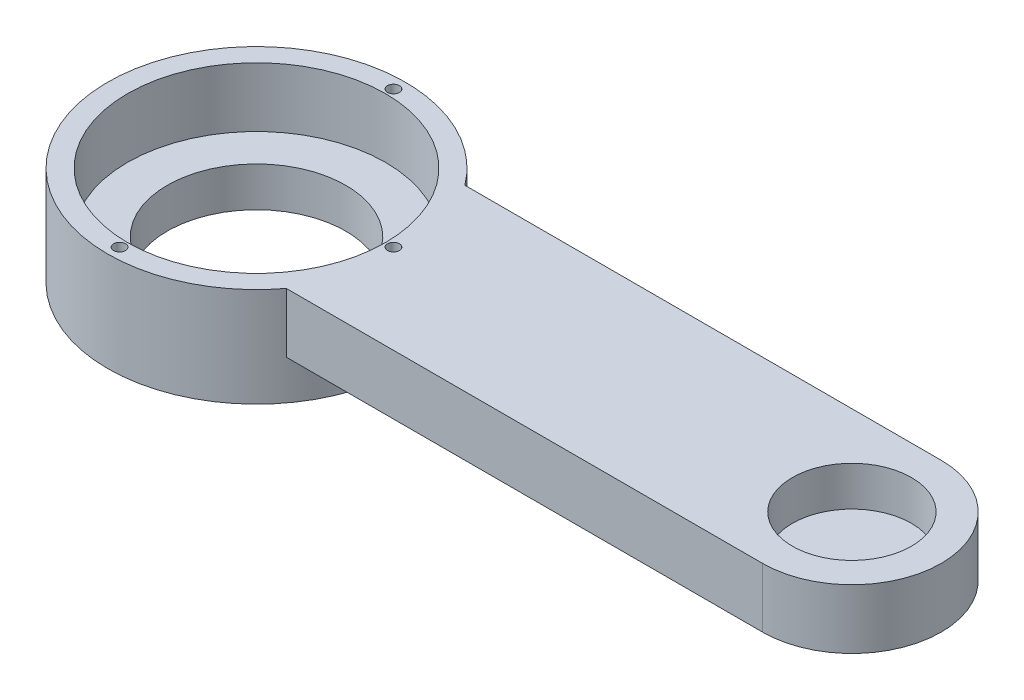
SolidWorks part; units mm, degrees
material "ABS"
ref_plane "Front Plane" through (0, 0, 0) normal (0, 0, 1) x (1, 0, 0)
ref_plane "Top Plane" through (0, 0, 0) normal (0, 1, 0) x (1, 0, 0)
ref_plane "Right Plane" through (0, 0, 0) normal (1, 0, 0) x (0, 0, -1)
sketch "Sketch2" plane through (0, 0, 0) normal (0, 1, 0) x (1, 0, 0)
  line L0 (0, 0) -> (150, 0) construction
  line L1 (0, 22.5) -> (150, 22.5)
  line L2 (0, -22.5) -> (150, -22.5)
  arc A0 (0, 22.5) -> (0, -22.5) centre (0, 0) ccw
  arc A1 (150, -22.5) -> (150, 22.5) centre (150, 0) ccw
  point P3 (75, 0)
  dimension "D1" = 150
  dimension "D2" = 45
extrude "Boss-Extrude1" add sketch "Sketch2" along normal blind 15
sketch "Sketch4" plane through (0, 15, 0) normal (0, 1, 0) x (1, 0, 0)
  circle A0 centre (0, 0) radius 37.5
  dimension "D1" = 75
extrude "Boss-Extrude2" add sketch "Sketch4" against normal blind 25
sketch "Sketch5" plane through (0, 15, 0) normal (0, 1, 0) x (1, 0, 0)
  circle A0 centre (0, 0) radius 22.5
  dimension "D1" = 45
extrude "Cut-Extrude1" cut sketch "Sketch5" against normal through all
sketch "Sketch6" plane through (0, 15, 0) normal (0, 1, 0) x (1, 0, 0)
  circle A1 centre (0, 0) radius 32.5
  dimension "D1" = 65
extrude "Cut-Extrude2" cut sketch "Sketch6" against normal offset from surface (15 mm away) 10 up to face at (0, -10, 22.5)
sketch "Sketch7" plane through (0, 0, 0) normal (0, -1, 0) x (1, 0, 0)
  circle A0 centre (150, 0) radius 15
  dimension "D1" = 30
extrude "Cut-Extrude3" cut sketch "Sketch7" against normal through all
sketch "Sketch8" plane through (0, 15, 0) normal (0, 1, 0) x (1, 0, 0)
  circle A0 centre (150, 0) radius 10
  dimension "D1" = 20
extrude "Cut-Extrude4" [suppressed] cut sketch "Sketch8" against normal through all both and the other way through all
sketch "Sketch9" plane through (0, 0, 0) normal (0, -1, 0) x (1, 0, 0)
  circle A0 centre (150, 0) radius 15 construction
  circle A1 centre (150, 0) radius 15
extrude "Boss-Extrude3" add sketch "Sketch9" against normal blind 5
sketch "Sketch10" plane through (0, 15, 0) normal (0, 1, 0) x (1, 0, 0)
  circle A0 centre (0, -34.5) radius 1.5 construction
  circle A1 centre (34.5, 0) radius 1.5 construction
  circle A2 centre (0, 34.5) radius 1.5 construction
  circle A3 centre (0, -34.5) radius 1.5
  circle A4 centre (34.5, 0) radius 1.5
  circle A5 centre (0, 34.5) radius 1.5
extrude "Cut-Extrude7" cut sketch "Sketch10" against normal blind 3
